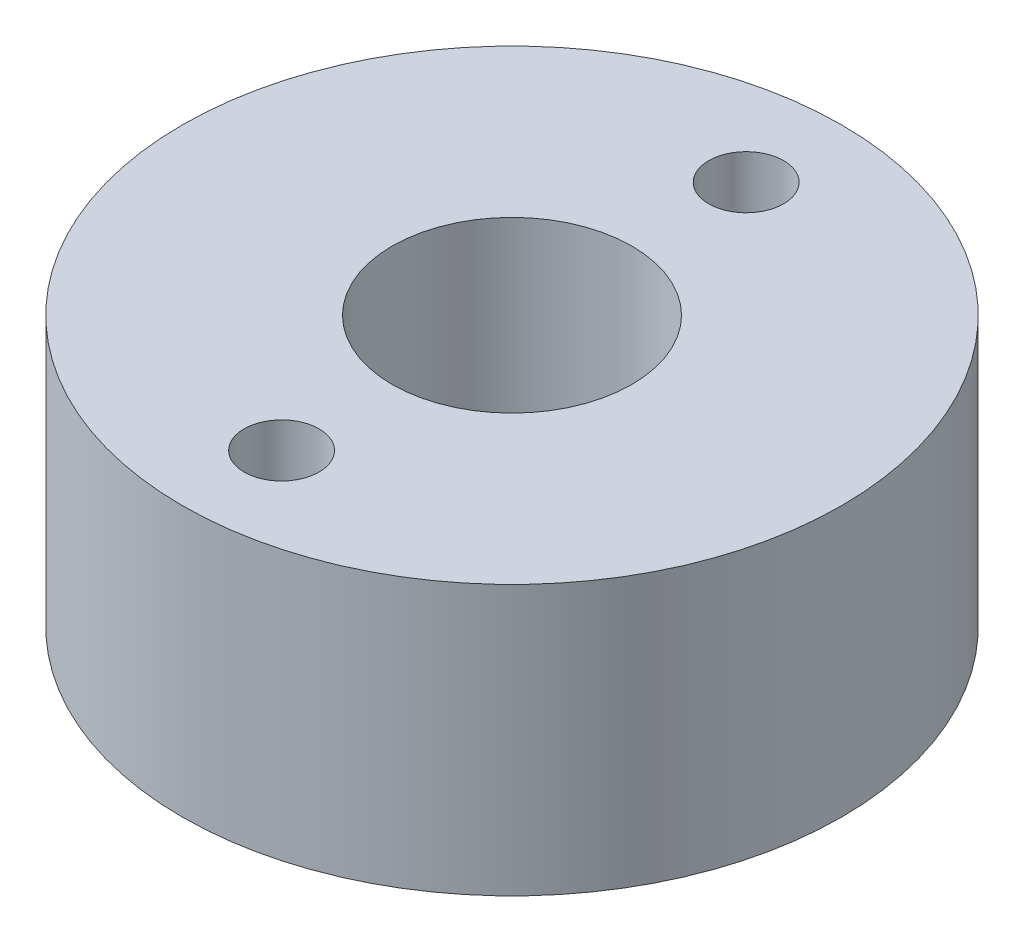
SolidWorks part; units mm, degrees
material "6061 Alloy"
ref_plane "Front Plane" through (0, 0, 0) normal (0, 0, 1) x (1, 0, 0)
ref_plane "Top Plane" through (0, 0, 0) normal (0, 1, 0) x (1, 0, 0)
ref_plane "Right Plane" through (0, 0, 0) normal (1, 0, 0) x (0, 0, -1)
sketch "Sketch2" plane through (0, 0, 0) normal (0, 1, 0) x (1, 0, 0)
  circle A0 centre (-115.8776, -47.3165) radius 4
  circle A1 centre (-115.8776, -47.3165) radius 11
  dimension "D1" = 8
  dimension "D2" = 22
extrude "Boss-Extrude2" add sketch "Sketch2" along normal blind 9
sketch "Sketch3" plane through (0, 9, 0) normal (0, 1, 0) x (1, 0, 0)
  line L0 (-126.8776, -47.3165) -> (-104.7526, -47.3165) construction
  line L1 (-115.8776, -58.3165) -> (-115.8776, -36.3165) construction
  circle A1 centre (-115.8776, -47.3165) radius 11 construction
  circle A2 centre (-115.8776, -47.3165) radius 11.125 construction
  circle A5 centre (-115.8151, -47.3165) radius 7.75 construction
  circle A6 centre (-115.8151, -39.5665) radius 1.25
  circle A7 centre (-115.8151, -55.0665) radius 1.25
  dimension "D1" = 15.5
  dimension "D2" = 2.5
extrude "Cut-Extrude1" cut sketch "Sketch3" against normal through all
equation "\"D1@Sketch2\"=\"ADP_CollarBore\""
equation "\"D2@Sketch2\"=\"ADP_CollarOD\""
equation "\"D1@Boss-Extrude2\"=\"ADP_CollarWidth\""
equation "\"D1@Cut-Extrude1\"=\"SEAT_TapDrillDia\""
equation "\"D1@Sketch3\"=\"SEAT_ScrewBCDia\""
equation "\"D2@Sketch3\"=\"SEAT_TapDrillDia\""
equation "\"____ GENERATED PART EXPORTS ____\" = 0"
equation "\"SYS_VersionTag\" = 2"
equation "\"ADP_CollarBore\" = 8mm"
equation "\"ADP_CollarOD\" = 22mm"
equation "\"ADP_CollarWidth\" = 9mm"
equation "\"SEAT_ScrewBCDia\" = 15.5mm"
equation "\"SEAT_TapDrillDia\" = 2.5mm"
